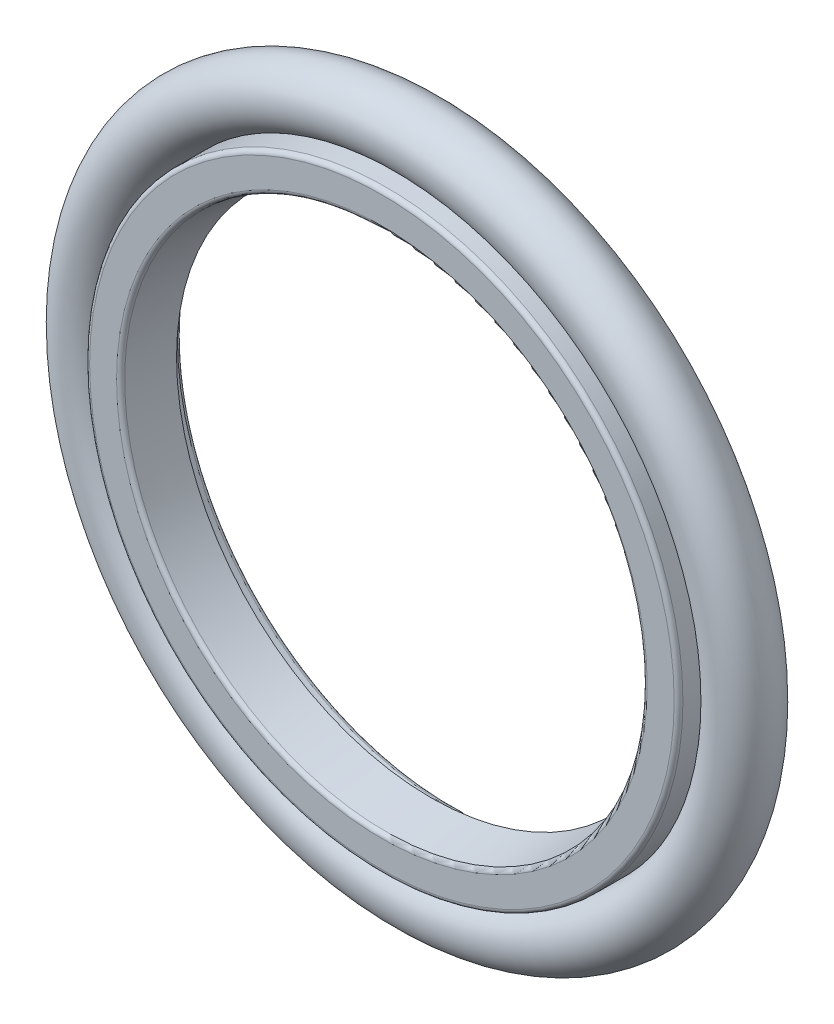
SolidWorks part; units mm, degrees
material "PTFE+NBR"
ref_plane "Front Plane" through (0, 0, 0) normal (0, 0, 1) x (1, 0, 0)
ref_plane "Top Plane" through (0, 0, 0) normal (0, 1, 0) x (1, 0, 0)
ref_plane "Right Plane" through (0, 0, 0) normal (1, 0, 0) x (0, 0, -1)
sketch "Sketch1" plane through (0, 0, 0) normal (1, 0, 0) x (0, 0, -1)
  line L0 (0, 0) -> (11.2675, 0) construction
  line L1 (0.25, 16.9) -> (3.75, 16.9)
  line L2 (0, 16.65) -> (0, 15.1168)
  line L3 (4, 16.65) -> (4, 15.65)
  line L4 (3.75, 15.4) -> (3.2, 15.4)
  line L5 (3.2, 15.4) -> (2.8, 14.5)
  line L6 (2.8, 14.5) -> (0.2146, 14.8693)
  arc A0 (0, 15.1168) -> (0.2146, 14.8693) centre (0.25, 15.1168) ccw
  arc A1 (4, 15.65) -> (3.75, 15.4) centre (3.75, 15.65) cw
  arc A2 (0.25, 16.9) -> (0, 16.65) centre (0.25, 16.65) ccw
  arc A3 (4, 16.65) -> (3.75, 16.9) centre (3.75, 16.65) ccw
  circle A4 centre (2, 18.65) radius 1.75 construction
  point P11 (0, 14.9)
  point P20 (2.1637, 14.25)
  point P21 (0, 0)
  point P22 (1.5113, 15)
  point P23 (2, 16.9)
  point P24 (2.1637, 13.75)
  point P25 (1.5, 15)
  dimension "D8" = 0.25
  dimension "D12" = 40.8
  dimension "D13" = 3.5
  dimension "D14" = 0
  dimension "D1" = 0.8
  dimension "D2" = 1.2
  dimension "D3" = 4
  dimension "D4" = 2
  dimension "D5" = 33.8
  dimension "D6" = 2.4
  dimension "D7" = 1.5
  dimension "D9" = 29
  dimension "D10" = 29.8
  dimension "D11" = 30.8
  dimension "D15" = 29
revolve "Revolve1" add sketch "Sketch1" angle 360 about L0
sketch "Sketch2" plane through (0, 0, 0) normal (1, 0, 0) x (0, 0, -1)
  line L0 (2, 16.9) -> (2, 10.528) construction
  line L1 (3.75, 16.9) -> (0.25, 16.9) construction
  line L2 (0, 0) -> (10.3771, 0) construction
  circle A0 centre (2, 18.65) radius 1.75
  dimension "D1" = 3.5
  dimension "D2" = 40.8
revolve "Revolve2" add sketch "Sketch2" angle 360 about L2
